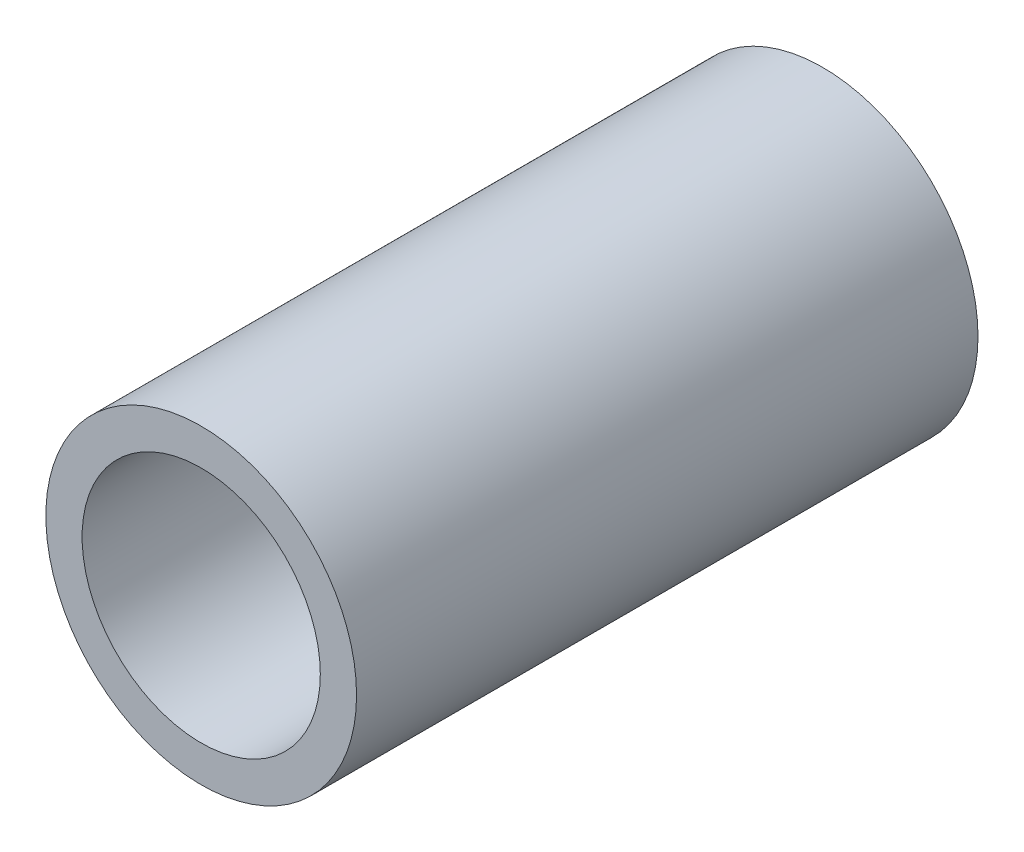
SolidWorks part; units mm, degrees
ref_plane "Plano frontal" through (0, 0, 0) normal (0, 0, 1) x (1, 0, 0)
ref_plane "Plano superior" through (0, 0, 0) normal (0, 1, 0) x (1, 0, 0)
ref_plane "Plano direito" through (0, 0, 0) normal (1, 0, 0) x (0, 0, -1)
sketch "Esboço1" plane through (0, 0, 0) normal (0, 0, 1) x (1, 0, 0)
  circle A0 centre (0, 0) radius 3
  dimension "D1" = 6
extrude "Ressalto-extrusão1" add sketch "Esboço1" along normal blind 12
sketch "Esboço2" plane through (0, 0, 12) normal (0, 0, 1) x (1, 0, 0)
  circle A0 centre (0, 0) radius 2.3
  dimension "D1" = 4.6
extrude "Corte-extrusão1" cut sketch "Esboço2" against normal blind 8.5
sketch "Esboço3" plane through (0, 0, 3.5) normal (0, 0, 1) x (1, 0, 0)
  circle A0 centre (0, 0) radius 2
  dimension "D1" = 4
extrude "Corte-extrusão2" cut sketch "Esboço3" against normal up to next
